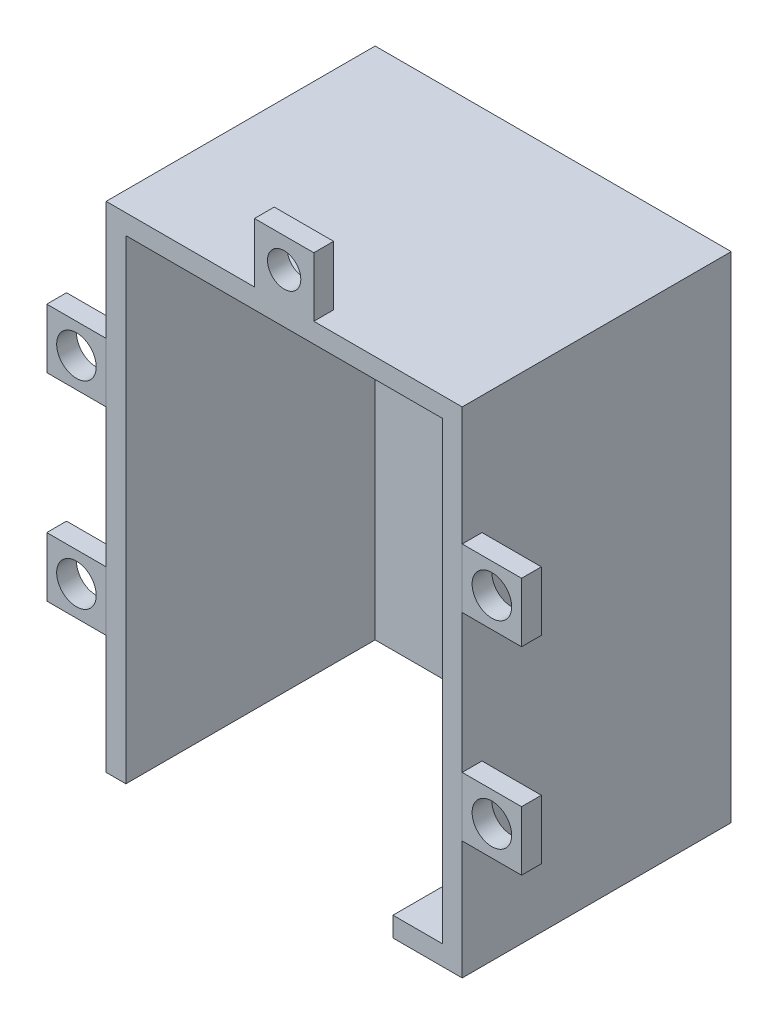
SolidWorks part; units mm, degrees
material "ABS PC"
ref_plane "Front Plane" through (0, 0, 0) normal (0, 0, 1) x (1, 0, 0)
ref_plane "Top Plane" through (0, 0, 0) normal (0, 1, 0) x (1, 0, 0)
ref_plane "Right Plane" through (0, 0, 0) normal (1, 0, 0) x (0, 0, -1)
sketch "Sketch1" plane through (0, 0, 0) normal (0, 0, 1) x (1, 0, 0)
  line L0 (0, 0) -> (0, 50)
  line L1 (0, 50) -> (36, 50)
  line L2 (36, 50) -> (36, 0)
  line L3 (36, 0) -> (0, 0)
  dimension "D1" = 50
  dimension "D2" = 36
extrude "Boss-Extrude1" add sketch "Sketch1" against normal blind 27.2
sketch "Sketch2" plane through (0, 0, 0) normal (0, 0, 1) x (1, 0, 0)
  line L0 (18, 50) -> (18, 0) construction
  line L1 (36, 50) -> (0, 50) construction
  line L2 (0, 0) -> (36, 0) construction
  circle A0 centre (18, 33) radius 3
  dimension "D1" = 6
  dimension "D2" = 17
extrude "Cut-Extrude1" cut sketch "Sketch2" against normal up to next
sketch "Sketch8" plane through (0, 0, 0) normal (0, 0, 1) x (1, 0, 0)
  line L0 (2, 48) -> (34, 48)
  line L1 (34, 48) -> (34, 2)
  line L2 (34, 2) -> (2, 2)
  line L3 (2, 2) -> (2, 48)
  line L4 (36, 50) -> (0, 50) construction
  line L5 (0, 50) -> (0, 0) construction
  dimension "D1" = 32
  dimension "D2" = 46
  dimension "D3" = 2
  dimension "D4" = 2
extrude "Cut-Extrude2" cut sketch "Sketch8" against normal blind 25.2
sketch "Sketch9" plane through (0, 0, -27.2) normal (0, 0, -1) x (-1, 0, 0)
  circle A0 centre (-18, 33) radius 5.25 construction
  dimension "D1" = 10.5
sketch "Sketch10" plane through (0, 0, -27.2) normal (0, 0, -1) x (-1, 0, 0)
  circle A0 centre (-18, 20.75) radius 7 construction
  dimension "D1" = 14
  dimension "D2" = 12.25
sketch "Sketch11" plane through (0, 0, -27.2) normal (0, 0, -1) x (-1, 0, 0)
  line L0 (-13, 13.55) -> (-23, 13.55) construction
  line L1 (-23, 13.55) -> (-23, 22.75) construction
  line L2 (-23, 22.75) -> (-13, 22.75) construction
  line L3 (-13, 22.75) -> (-13, 13.55) construction
  dimension "D1" = 7.2
  dimension "D2" = 2
  dimension "D3" = 5
  dimension "D4" = 5
sketch "Sketch12" plane through (0, 0, -27.2) normal (0, 0, -1) x (-1, 0, 0)
  line L0 (-13.5, 13.55) -> (-13.5, 12.95)
  line L1 (-13, 13.55) -> (-23, 13.55) construction
  line L2 (-13.5, 12.95) -> (-14.5, 12.95)
  line L3 (-14.5, 12.95) -> (-14.5, 13.55)
  line L4 (-14.5, 13.55) -> (-13.5, 13.55)
  line L5 (-17.5, 13.55) -> (-18.5, 13.55)
  line L6 (-18.5, 13.55) -> (-18.5, 12.95)
  line L7 (-18.5, 12.95) -> (-17.5, 12.95)
  line L8 (-17.5, 12.95) -> (-17.5, 13.55)
  line L9 (-21.5, 13.55) -> (-21.5, 12.95)
  line L10 (-21.5, 12.95) -> (-22.5, 12.95)
  line L11 (-22.5, 12.95) -> (-22.5, 13.55)
  line L12 (-22.5, 13.55) -> (-21.5, 13.55)
  line L13 (-12.6, 22.75) -> (-12.6, 23.95)
  line L14 (-12.6, 23.95) -> (-13.4, 23.95)
  line L15 (-13.4, 23.95) -> (-13.4, 22.75)
  line L16 (-13, 22.75) -> (-13, 13.55) construction
  line L17 (-13.4, 22.75) -> (-12.6, 22.75)
  line L18 (-23.4, 22.75) -> (-22.6, 22.75)
  line L19 (-22.6, 22.75) -> (-22.6, 23.95)
  line L20 (-22.6, 23.95) -> (-23.4, 23.95)
  line L21 (-23.4, 23.95) -> (-23.4, 22.75)
  line L22 (-23, 13.55) -> (-23, 22.75) construction
  line L23 (-23, 22.75) -> (-13, 22.75) construction
  dimension "D1" = 1
  dimension "D2" = 0.6
  dimension "D3" = 0.5
  dimension "D4" = 1
  dimension "D5" = 0.6
  dimension "D6" = 4.5
  dimension "D7" = 1
  dimension "D8" = 0.6
  dimension "D9" = 0.5
  dimension "D10" = 1.2
  dimension "D11" = 0.8
  dimension "D12" = 0.8
  dimension "D13" = 1.2
  dimension "D14" = 0.4
  dimension "D15" = 0.4
extrude "Cut-Extrude3" cut sketch "Sketch12" against normal blind 25.2
sketch "Sketch14" plane through (0, 0, 0) normal (0, -1, 0) x (1, 0, 0)
  line L0 (2, 0) -> (2, -25.2)
  line L1 (0, 0) -> (36, 0) construction
  line L2 (2, -25.2) -> (34, -25.2)
  line L3 (34, -25.2) -> (34, 0)
  line L4 (34, 0) -> (2, 0)
  line L5 (0, -27.2) -> (0, 0) construction
  line L6 (0, -27.2) -> (36, -27.2) construction
  line L7 (36, -27.2) -> (36, 0) construction
  dimension "D1" = 2
  dimension "D2" = 2
  dimension "D3" = 2
extrude "Cut-Extrude4" cut sketch "Sketch14" against normal blind 25.2
sketch "Sketch16" plane through (0, 0, 0) normal (0, -1, 0) x (-1, 0, 0)
  line L1 (-34, 25.2) -> (-29, 25.2)
  line L2 (-34, 25.2) -> (-34, 0)
  line L3 (-34, 0) -> (-29, 0)
  line L4 (-29, 25.2) -> (-29, 0)
  dimension "D1" = 5
extrude "Boss-Extrude2" add sketch "Sketch16" against normal blind 2
sketch "Sketch17" plane through (0, 0, 0) normal (0, 0, 1) x (1, 0, 0)
  line L0 (36, 38) -> (42, 38)
  line L1 (36, 0) -> (36, 50) construction
  line L2 (42, 38) -> (42, 32)
  line L3 (42, 32) -> (36, 32)
  line L4 (36, 32) -> (36, 38)
  point P4 (42, 35)
  dimension "D1" = 6
  dimension "D2" = 6
  dimension "D3" = 15
extrude "Boss-Extrude3" add sketch "Sketch17" against normal blind 2 separate body
sketch "Sketch18" plane through (0, 0, 0) normal (0, 0, 1) x (1, 0, 0)
  line L0 (42, 35) -> (36, 35) construction
  line L1 (42, 32) -> (42, 38) construction
  line L2 (36, 38) -> (36, 32) construction
  circle A0 centre (39, 35) radius 2
  dimension "D1" = 4
extrude "Cut-Extrude5" cut sketch "Sketch18" against normal blind 2
ref_plane "Plane4" through (0, 25, 0) normal (0, -1, 0) x (-1, 0, 0)
mirror "Mirror1" about plane through (0, 25, 0) normal (0, -1, 0) of bodies 108
ref_plane "Plane5" through (18, 0, 0) normal (-1, 0, 0) x (0, 0, 1)
mirror "Mirror2" about plane through (18, 0, 0) normal (-1, 0, 0) of bodies 108 109
sketch "Sketch20" plane through (0, 0, 0) normal (0, 0, 1) x (1, 0, 0)
  line L0 (21, 50) -> (21, 56)
  line L1 (36, 50) -> (0, 50) construction
  line L2 (21, 56) -> (15, 56)
  line L3 (15, 56) -> (15, 50)
  line L4 (15, 50) -> (21, 50)
  dimension "D1" = 6
  dimension "D2" = 6
  dimension "D3" = 15
extrude "Boss-Extrude4" add sketch "Sketch20" against normal blind 2
sketch "Sketch21" plane through (0, 0, 0) normal (0, 0, 1) x (1, 0, 0)
  line L0 (21, 50) -> (21, 56) construction
  line L2 (21, 56) -> (15, 56) construction
  circle A0 centre (18, 53) radius 1.6844
  dimension "D1" = 3
  dimension "D2" = 3
extrude "Cut-Extrude6" cut sketch "Sketch21" against normal up to next (2 mm away)
